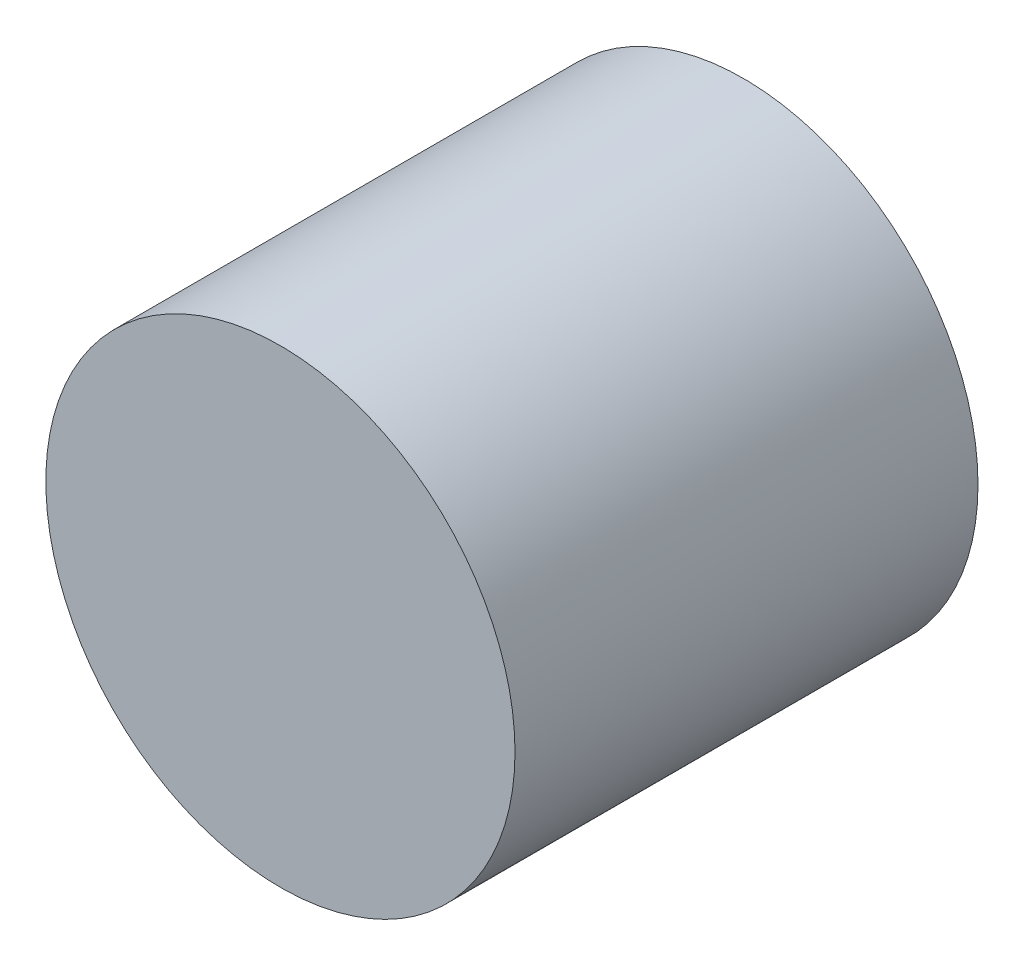
SolidWorks part; units mm, degrees
ref_plane "Alzado" through (0, 0, 0) normal (0, 0, 1) x (1, 0, 0)
ref_plane "Planta" through (0, 0, 0) normal (0, 1, 0) x (1, 0, 0)
ref_plane "Vista lateral" through (0, 0, 0) normal (1, 0, 0) x (0, 0, -1)
sketch "Croquis1" plane through (0, 0, 0) normal (0, 0, 1) x (1, 0, 0)
  circle A0 centre (-4.9763, -25.8) radius 15
  dimension "D1" = 30
  dimension "D2" = 4.9763
  dimension "D3" = 25.8
extrude "Saliente-Extruir1" add sketch "Croquis1" along normal up to vertex (21.6042 mm away) and the other way blind 8
